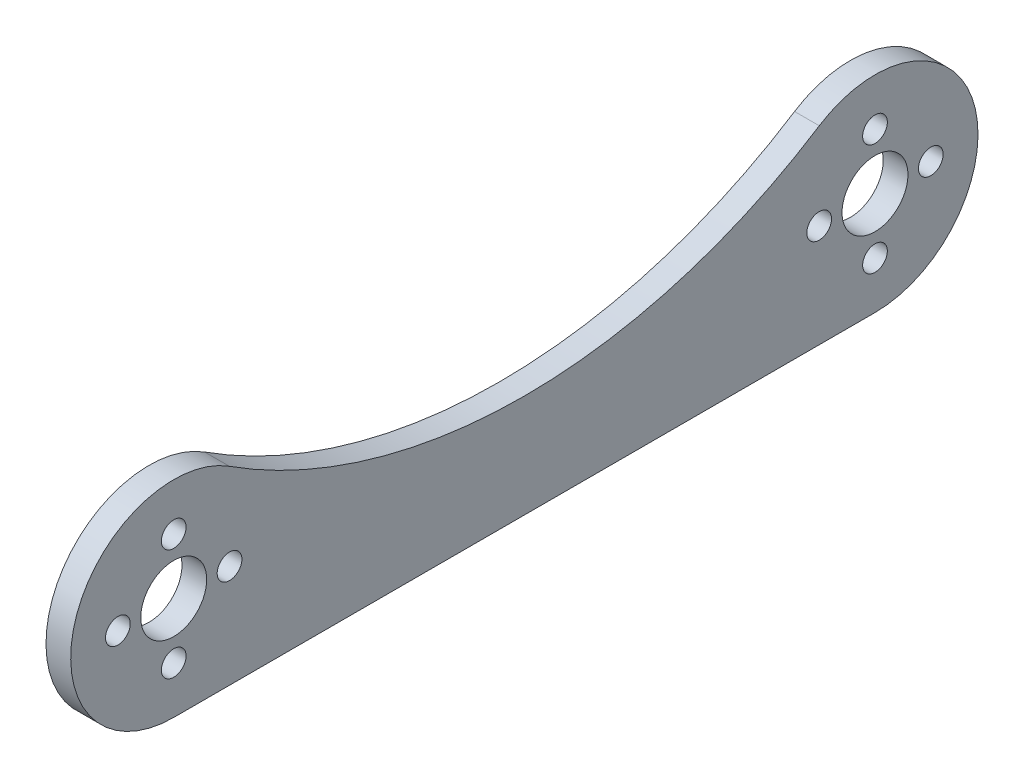
SolidWorks part; units mm, degrees
ref_plane "Front Plane" through (0, 0, 0) normal (0, 0, 1) x (1, 0, 0)
ref_plane "Top Plane" through (0, 0, 0) normal (0, 1, 0) x (1, 0, 0)
ref_plane "Right Plane" through (0, 0, 0) normal (1, 0, 0) x (0, 0, -1)
sketch "Sketch1" plane through (0, 0, 0) normal (1, 0, 0) x (0, 0, -1)
  line L0 (-82.3071, 0) -> (103.5477, 0) construction
  line L1 (0, 66.1701) -> (0, -34.267) construction
  line L2 (-42.55, -12.5) -> (42.55, -12.5)
  arc A0 (-35.7892, 10.5139) -> (-42.55, -12.5) centre (-42.55, 0) ccw
  circle A1 centre (-42.55, 0) radius 4
  circle A2 centre (-42.55, 0) radius 6.775 construction
  circle A3 centre (-35.775, 0) radius 1.5
  circle A4 centre (-42.55, -6.775) radius 1.5
  circle A5 centre (-49.325, 0) radius 1.5
  circle A6 centre (-42.55, 6.775) radius 1.5
  circle A7 centre (42.55, 0) radius 6.775 construction
  circle A8 centre (42.55, 6.775) radius 1.5
  circle A9 centre (49.325, 0) radius 1.5
  circle A10 centre (42.55, -6.775) radius 1.5
  circle A11 centre (35.775, 0) radius 1.5
  circle A12 centre (42.55, 0) radius 4
  arc A13 (35.7892, 10.5139) -> (42.55, -12.5) centre (42.55, 0) cw
  arc A14 (-35.7892, 10.5139) -> (35.7892, 10.5139) centre (0, 66.1701) ccw
  point P20 (-42.55, 0)
  point P32 (42.55, 0)
  dimension "D1" = 25
  dimension "D2" = 8
  dimension "D3" = 3
  dimension "D5" = 13.55
  dimension "D6" = 85.1
  dimension "D4" = 4
extrude "Boss-Extrude1" add sketch "Sketch1" along normal blind 3
